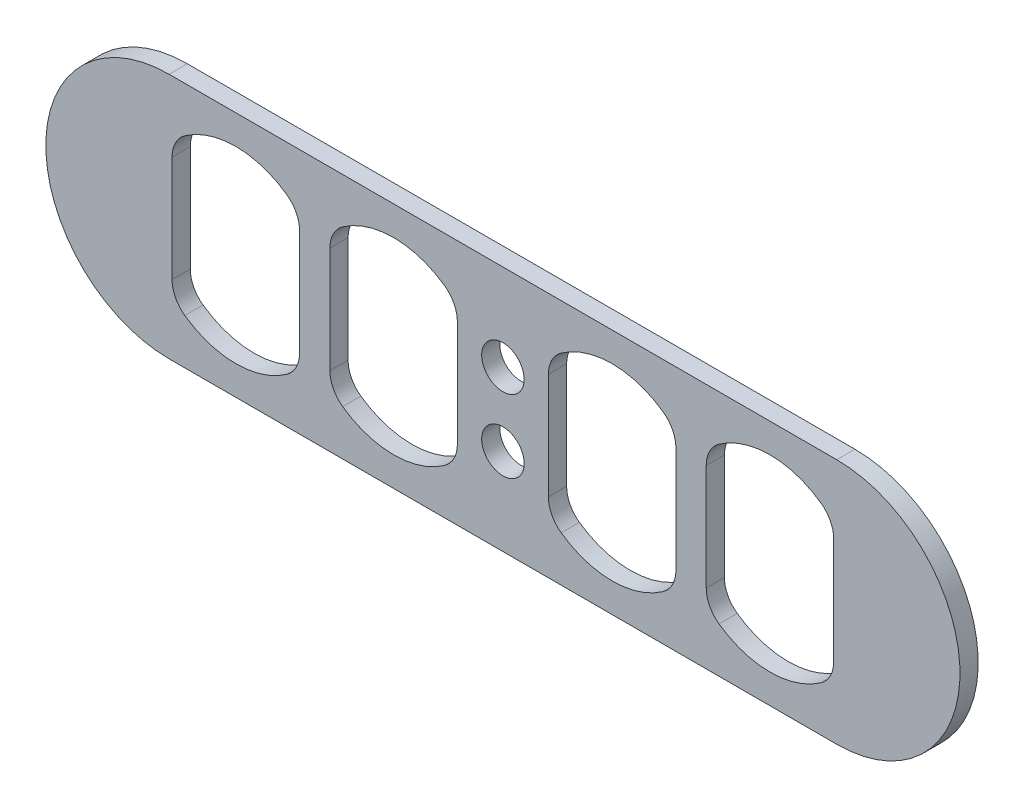
SolidWorks part; units mm, degrees
ref_plane "Plan de face" through (0, 0, 0) normal (0, 0, 1) x (1, 0, 0)
ref_plane "Plan de dessus" through (0, 0, 0) normal (0, 1, 0) x (1, 0, 0)
ref_plane "Plan de droite" through (0, 0, 0) normal (1, 0, 0) x (0, 0, -1)
sketch "Esquisse1" plane through (0, 0, 0) normal (0, 0, 1) x (1, 0, 0)
  line L0 (-55, 0) -> (55, 0) construction
  line L5 (-55, 22.5) -> (55, 22.5) construction
  line L6 (-55, -22.5) -> (55, -22.5) construction
  line L7 (-55, 20.3) -> (55, 20.3)
  line L8 (-55, -20.3) -> (55, -20.3)
  arc A0 (-55, 22.5) -> (-55, -22.5) centre (-55, 0) ccw construction
  arc A1 (55, -22.5) -> (55, 22.5) centre (55, 0) ccw construction
  arc A2 (55, -20.3) -> (55, 20.3) centre (55, 0) ccw
  arc A3 (-55, 20.3) -> (-55, -20.3) centre (-55, 0) ccw
  point P2 (0, 0)
  dimension "D1" = 110
  dimension "D2" = 45
  dimension "D3" = 2.2
extrude "Boss.-Extru.1" add sketch "Esquisse1" along normal blind 3
sketch "Esquisse2" plane through (0, 0, 3) normal (0, 0, 1) x (1, 0, 0)
  line L0 (0, 0) -> (-7.5, 0) construction
  line L1 (-7.5, -8.746) -> (-7.5, 8.746)
  line L2 (-33.5, -8.746) -> (-33.5, 8.746)
  line L3 (-28.5, 8.746) -> (-28.5, -8.746)
  line L4 (-54.5, 8.746) -> (-54.5, -8.746)
  line L5 (0, -55) -> (0, 55) construction
  line L6 (28.5, 8.746) -> (28.5, -8.746)
  line L7 (7.5, -8.746) -> (7.5, 8.746)
  line L8 (54.5, 8.746) -> (54.5, -8.746)
  line L9 (33.5, -8.746) -> (33.5, 8.746)
  line L10 (0, 6) -> (0, -6) construction
  arc A2 (-26.3947, 12.8228) -> (-9.6053, 12.8228) centre (-18, 1) cw
  arc A3 (-26.3947, -12.8228) -> (-9.6053, -12.8228) centre (-18, -1) ccw
  arc A4 (-28.5, -8.746) -> (-26.3947, -12.8228) centre (-23.5, -8.746) ccw
  arc A5 (-7.5, -8.746) -> (-9.6053, -12.8228) centre (-12.5, -8.746) cw
  arc A6 (-7.5, 8.746) -> (-9.6053, 12.8228) centre (-12.5, 8.746) ccw
  arc A7 (-26.3947, 12.8228) -> (-28.5, 8.746) centre (-23.5, 8.746) ccw
  arc A8 (-52.3947, 12.8228) -> (-35.6053, 12.8228) centre (-44, 1) cw
  arc A9 (-33.5, 8.746) -> (-35.6053, 12.8228) centre (-38.5, 8.746) ccw
  arc A10 (-33.5, -8.746) -> (-35.6053, -12.8228) centre (-38.5, -8.746) cw
  arc A11 (-52.3947, -12.8228) -> (-35.6053, -12.8228) centre (-44, -1) ccw
  arc A12 (-54.5, -8.746) -> (-52.3947, -12.8228) centre (-49.5, -8.746) ccw
  arc A13 (-52.3947, 12.8228) -> (-54.5, 8.746) centre (-49.5, 8.746) ccw
  arc A14 (26.3947, 12.8228) -> (28.5, 8.746) centre (23.5, 8.746) cw
  arc A15 (28.5, -8.746) -> (26.3947, -12.8228) centre (23.5, -8.746) cw
  arc A16 (26.3947, -12.8228) -> (9.6053, -12.8228) centre (18, -1) cw
  arc A17 (7.5, -8.746) -> (9.6053, -12.8228) centre (12.5, -8.746) ccw
  arc A18 (7.5, 8.746) -> (9.6053, 12.8228) centre (12.5, 8.746) cw
  arc A19 (26.3947, 12.8228) -> (9.6053, 12.8228) centre (18, 1) ccw
  arc A20 (52.3947, 12.8228) -> (54.5, 8.746) centre (49.5, 8.746) cw
  arc A21 (54.5, -8.746) -> (52.3947, -12.8228) centre (49.5, -8.746) cw
  arc A22 (52.3947, -12.8228) -> (35.6053, -12.8228) centre (44, -1) cw
  arc A23 (33.5, -8.746) -> (35.6053, -12.8228) centre (38.5, -8.746) ccw
  arc A24 (33.5, 8.746) -> (35.6053, 12.8228) centre (38.5, 8.746) cw
  arc A25 (52.3947, 12.8228) -> (35.6053, 12.8228) centre (44, 1) ccw
  circle A26 centre (0, 6) radius 3.5
  circle A27 centre (0, -6) radius 3.5
  point P6 (-7.5, 0)
  point P13 (-28.5, -11)
  point P16 (-7.5, -11)
  point P19 (-7.5, 11)
  point P22 (-28.5, 11)
  point P73 (0, 0)
  dimension "D4" = 31
  dimension "D5" = 5
  dimension "D8" = 7
  dimension "D1" = 22
  dimension "D2" = 21
  dimension "D3" = 18
  dimension "D7" = 12
  dimension "D6" = 2
extrude "Enlèv. mat.-Extru.1" cut sketch "Esquisse2" against normal through all
